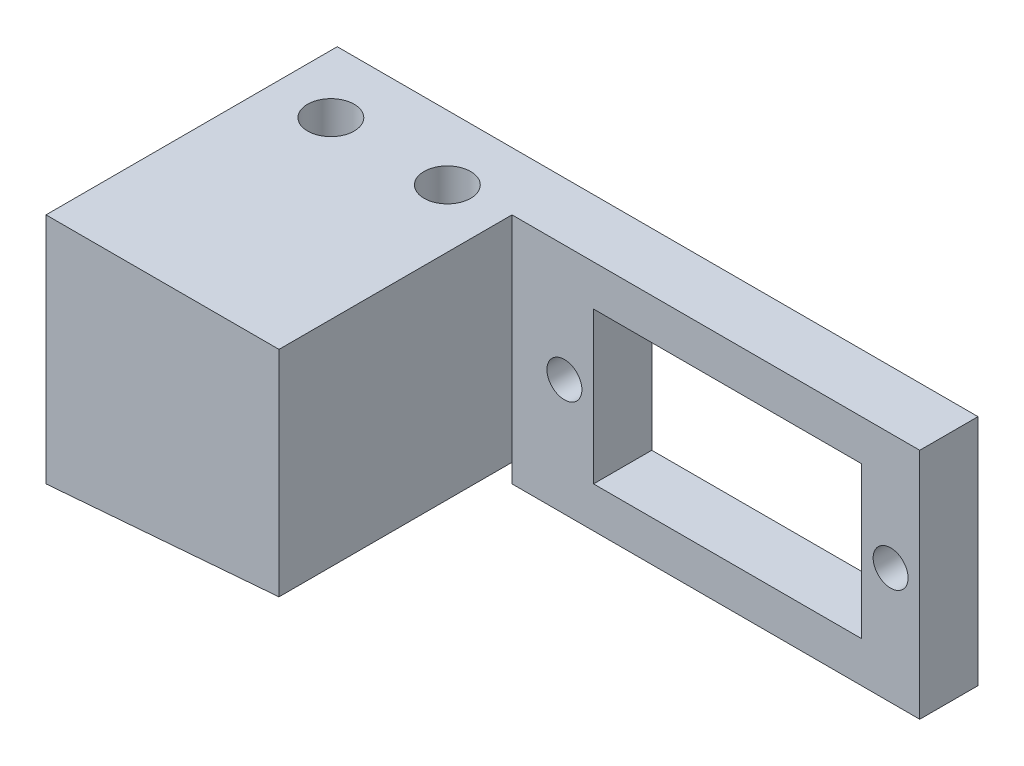
SolidWorks part; units mm, degrees
ref_plane "Plan de face" through (0, 0, 0) normal (0, 0, 1) x (1, 0, 0)
ref_plane "Plan de dessus" through (0, 0, 0) normal (0, 1, 0) x (1, 0, 0)
ref_plane "Plan de droite" through (0, 0, 0) normal (1, 0, 0) x (0, 0, -1)
sketch "Esquisse1" plane through (0, 0, 0) normal (0, 0, 1) x (1, 0, 0)
  line L1 (-28.3333, 8.3333) -> (26.6667, 8.3333)
  line L2 (-28.3333, 8.3333) -> (-28.3333, -11.6667)
  line L3 (-28.3333, -11.6667) -> (26.6667, -11.6667)
  line L4 (26.6667, 8.3333) -> (26.6667, -11.6667)
  dimension "D1" = 20
  dimension "D2" = 55
extrude "Boss.-Extru.1" add sketch "Esquisse1" along normal blind 5
sketch "Esquisse3" plane through (0, 0, 5) normal (0, 0, 1) x (1, 0, 0)
  line L0 (26.6667, -11.6667) -> (26.6667, 8.3333) construction
  line L1 (21.6667, 4.8333) -> (-1.3333, 4.8333)
  line L2 (21.6667, 4.8333) -> (21.6667, -8.1667)
  line L3 (21.6667, -8.1667) -> (-1.3333, -8.1667)
  line L4 (-1.3333, 4.8333) -> (-1.3333, -8.1667)
  line L5 (26.6667, 8.3333) -> (-28.3333, 8.3333) construction
  line L6 (-28.3333, -11.6667) -> (26.6667, -11.6667) construction
  circle A0 centre (24.1667, -1.6667) radius 1.5
  circle A1 centre (-3.8333, -1.6667) radius 1.5
  dimension "D5" = 10
  dimension "D6" = 10
  dimension "D7" = 3
  dimension "D8" = 3
  dimension "D9" = 2.5
  dimension "D10" = 2.5
  dimension "D1" = 23
  dimension "D2" = 13
  dimension "D3" = 5
  dimension "D4" = 3.5
extrude "Enlèv. mat.-Extru.2" cut sketch "Esquisse3" against normal blind 20
sketch "Esquisse5" plane through (0, 0, 0) normal (0, 0, -1) x (-1, 0, 0)
  line L0 (28.3333, -11.6667) -> (28.3333, 8.3333)
  line L1 (28.3333, 8.3333) -> (8.3333, 8.3333)
  line L2 (-26.6667, 8.3333) -> (28.3333, 8.3333) construction
  line L3 (8.3333, 8.3333) -> (8.3333, -10.0667)
  line L4 (8.3333, -10.0667) -> (28.3333, -11.6667)
  line L5 (28.3333, -11.6667) -> (-26.6667, -11.6667) construction
  dimension "D1" = 1.6
  dimension "D2" = 20
extrude "Boss.-Extru.2" add sketch "Esquisse5" against normal blind 25
sketch "Esquisse2" plane through (0, 8.3333, 0) normal (0, 1, 0) x (1, 0, 0)
  line L1 (-28.3333, -25) -> (-28.3333, 0) construction
  circle A0 centre (-23.3333, -5.5481) radius 2
  circle A1 centre (-13.3333, -5.5481) radius 2
  dimension "D1" = 4
  dimension "D2" = 4
  dimension "D3" = 5
  dimension "D4" = 15
extrude "Enlèv. mat.-Extru.1" cut sketch "Esquisse2" against normal blind 20
sketch "Esquisse7" plane through (0, 0, 5) normal (0, 0, 1) x (1, 0, 0)
  line L0 (-8.3333, -10.0667) -> (-8.3333, -11.6667)
  line L1 (-28.3333, -11.6667) -> (-25.2568, -11.6667) construction
  line L2 (-8.3333, -11.6667) -> (-28.3333, -11.6667)
  line L3 (-28.3333, -11.6667) -> (-8.3333, -10.0667)
extrude "Enlèv. mat.-Extru.4" cut sketch "Esquisse7" against normal blind 15
